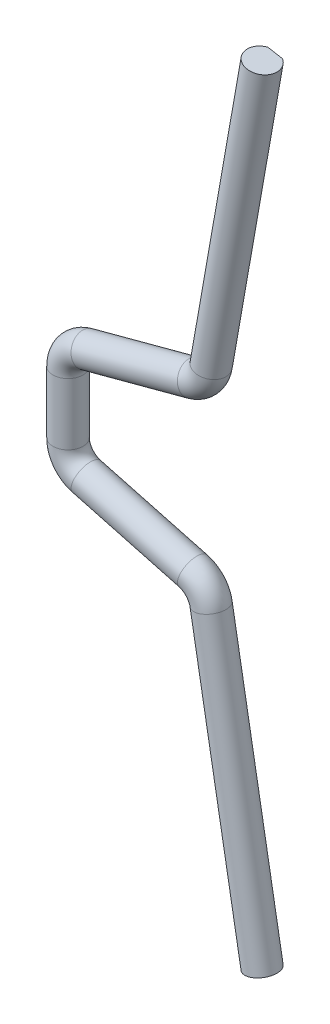
SolidWorks part; units mm, degrees
material "Простая углеродистая сталь"
ref_plane "Спереди" through (0, 0, 0) normal (0, 0, 1) x (1, 0, 0)
ref_plane "Сверху" through (0, 0, 0) normal (0, 1, 0) x (1, 0, 0)
ref_plane "Справа" through (0, 0, 0) normal (1, 0, 0) x (0, 0, -1)
sketch "Эскиз1" plane through (0, 0, 0) normal (0, 0, 1) x (1, 0, 0)
  line L0 (0, -1.5408) -> (0, 1.5408)
  line L1 (0.9265, 2.7482) -> (6.2308, 4.1695)
  line L2 (7.1383, 5.1599) -> (9.6836, 19.595)
  line L4 (9.6836, -19.595) -> (7.1383, -5.1599)
  line L5 (6.2308, -4.1695) -> (0.9265, -2.7482)
  line L6 (7, 4.3756) -> (7, -4.3756) construction
  line L7 (7, 0) -> (0, 0) construction
  line L8 (9.6836, 19.595) -> (9.6836, -19.595) construction
  line L9 (7, 0) -> (9.6836, 0) construction
  arc A0 (7.1383, 5.1599) -> (6.2308, 4.1695) centre (5.9073, 5.3769) cw
  arc A1 (7.1383, -5.1599) -> (6.2308, -4.1695) centre (5.9073, -5.3769) ccw
  arc A2 (0.9265, -2.7482) -> (0, -1.5408) centre (1.25, -1.5408) cw
  arc A3 (0, 1.5408) -> (0.9265, 2.7482) centre (1.25, 1.5408) cw
  point P18 (0, -2.5)
  point P21 (0, 2.5)
  dimension "D6" = 1.25
  dimension "D1" = 30
  dimension "D2" = 7
  dimension "D3" = 5
  dimension "D4" = 160
  dimension "D5" = 39.19
sketch "Эскиз2" plane through (0, 0, 0) normal (0, 1, 0) x (1, 0, 0)
  circle A0 centre (0, 0) radius 0.75
  dimension "D1" = 1.5
sweep "По траектории1" add profiles "Эскиз2" path "Эскиз1"
sketch "Эскиз3" plane through (0, 0, 0) normal (0, 1, 0) x (1, 0, 0)
  line L1 (-1, 0.75) -> (11, 0.75)
  line L2 (-1, 0.75) -> (-1, 0.65)
  line L3 (-1, 0.65) -> (11, 0.65)
  line L4 (11, 0.75) -> (11, 0.65)
  dimension "D1" = 0.75
  dimension "D2" = 0.1
  dimension "D3" = 1
  dimension "D4" = 12
extrude "Вырез-Вытянуть1" cut sketch "Эскиз3" against normal through all both and the other way through all
sketch "Эскиз4" plane through (0, 0, 0) normal (0, 1, 0) x (1, 0, 0)
  line L1 (-0.75, -0.75) -> (-0.65, -0.75)
  line L2 (-0.75, -0.75) -> (-0.75, 0.75)
  line L3 (-0.75, 0.75) -> (-0.65, 0.75)
  line L4 (-0.65, -0.75) -> (-0.65, 0.75)
  dimension "D1" = 0.75
  dimension "D2" = 1.5
  dimension "D3" = 0.75
  dimension "D4" = 0.1
extrude "Вырез-Вытянуть2" cut sketch "Эскиз4" against normal through all both and the other way through all
